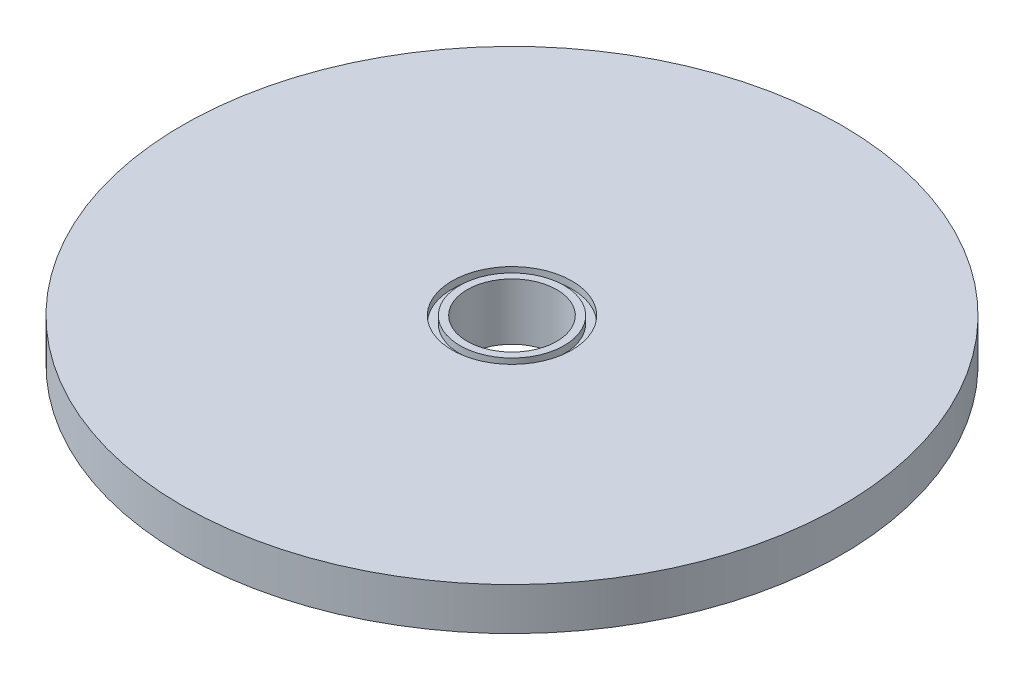
SolidWorks part; units mm, degrees
ref_plane "Front Plane" through (0, 0, 0) normal (0, 0, 1) x (1, 0, 0)
ref_plane "Top Plane" through (0, 0, 0) normal (0, 1, 0) x (1, 0, 0)
ref_plane "Right Plane" through (0, 0, 0) normal (1, 0, 0) x (0, 0, -1)
sketch "Sketch3" plane through (0, 0, 0) normal (0, 0, 1) x (1, 0, 0)
  line L0 (-9.4967, 0) -> (-47.57, 0)
  line L1 (-47.57, 0) -> (-47.57, 3)
  line L2 (-47.57, 3) -> (-69.85, 3)
  line L3 (-69.85, 3) -> (-69.85, 12)
  line L4 (-69.85, 12) -> (-9.4967, 12)
  line L5 (-9.4967, 12) -> (-9.4967, 0)
  line L6 (0, 0) -> (0, 15.8881) construction
  line L8 (-12.7, 12) -> (-11.049, 12)
  line L9 (-12.7, 12) -> (-12.7, 10.5)
  line L10 (-12.7, 10.5) -> (-11.049, 10.5)
  line L11 (-11.049, 12) -> (-11.049, 10.5)
  dimension "D1" = 69.85
  dimension "D2" = 12
  dimension "D3" = 3
  dimension "D4" = 47.57
  dimension "D5" = 9.4967
  dimension "D6" = 12.7
  dimension "D7" = 1.651
  dimension "D8" = 1.5
revolve "Revolve1" add sketch "Sketch3" angle 360 about L6
